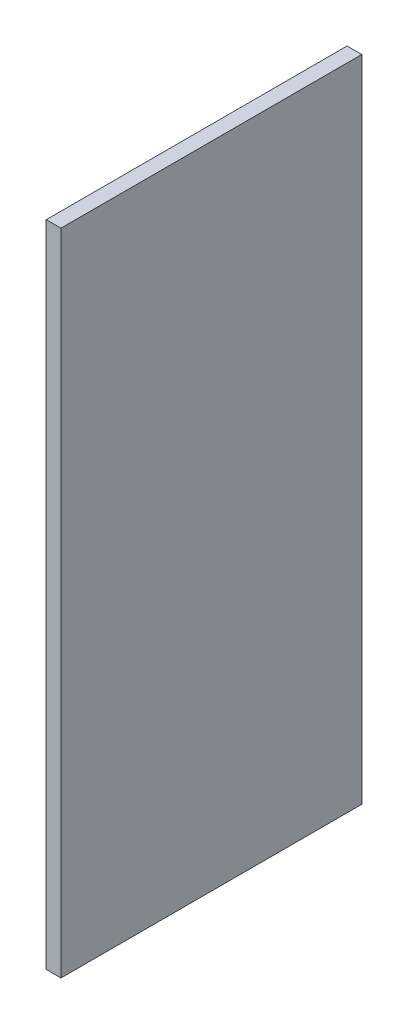
SolidWorks part; units mm, degrees
ref_plane "Front Plane" through (0, 0, 0) normal (0, 0, 1) x (1, 0, 0)
ref_plane "Top Plane" through (0, 0, 0) normal (0, 1, 0) x (1, 0, 0)
ref_plane "Right Plane" through (0, 0, 0) normal (1, 0, 0) x (0, 0, -1)
other "Configuration Table"
sketch "Sketch1" plane through (0, 0, 0) normal (0, 0, 1) x (1, 0, 0)
  line L1 (1.5, 201.5) -> (41.5, 201.5)
  line L2 (1.5, 201.5) -> (1.5, 1968.5)
  line L3 (1.5, 1968.5) -> (41.5, 1968.5)
  line L4 (41.5, 201.5) -> (41.5, 1968.5)
extrude "TOPPING_pu_yan_sol_1" add sketch "Sketch1" against normal blind 818.5 separate body
